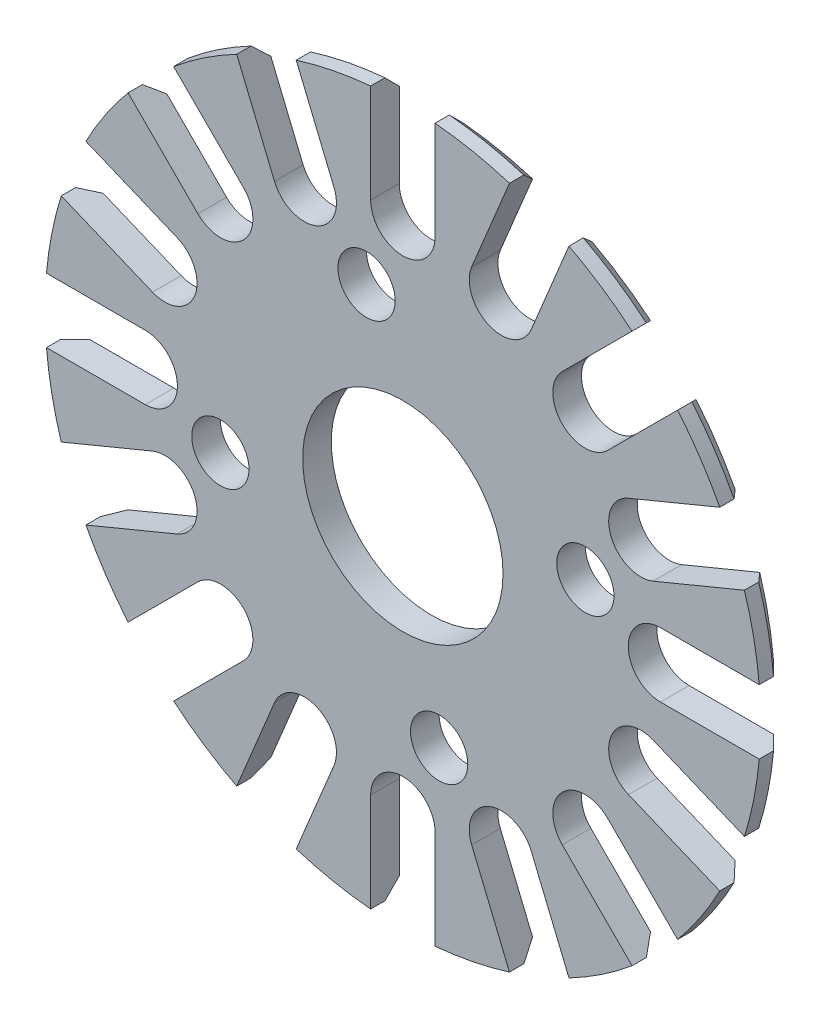
SolidWorks part; units mm, degrees
material "2A12"
ref_plane "前视基准面" through (0, 0, 0) normal (0, 0, 1) x (1, 0, 0)
ref_plane "上视基准面" through (0, 0, 0) normal (0, 1, 0) x (1, 0, 0)
ref_plane "右视基准面" through (0, 0, 0) normal (1, 0, 0) x (0, 0, -1)
sketch "草图1" plane through (0, 0, 0) normal (0, 0, 1) x (1, 0, 0)
  circle A0 centre (0, 0) radius 25
  dimension "D1" = 50
extrude "拉伸1" add sketch "草图1" along normal blind 2
sketch "草图2" plane through (0, 0, 2) normal (0, 0, 1) x (1, 0, 0)
  circle A0 centre (0, 0) radius 7
  dimension "D1" = 14
extrude "拉伸2" cut sketch "草图2" against normal blind 3
sketch "草图3" plane through (0, 0, 2) normal (0, 0, 1) x (1, 0, 0)
  line L0 (-2.5362, 12.7502) -> (0, 0) construction
  line L1 (0, 0) -> (0, 13) construction
  circle A0 centre (-2.5362, 12.7502) radius 2
  circle A1 centre (0, 0) radius 13 construction
  dimension "D1" = 26
  dimension "D2" = 4
  dimension "D3" = 11.25
extrude "拉伸3" cut sketch "草图3" against normal blind 3
pattern_circular "阵列(圆周)1" count 4 every 90 about axis through (0, 0, 0) along (0, 0, 1) of "拉伸3"
chamfer "倒角1" distance 1 angle 45 1 edges at (25, 0, 0)
sketch "草图4" plane through (0, 0, 2) normal (0, 0, 1) x (1, 0, 0)
  line L0 (-18, 2.25) -> (-24.8985, 2.25)
  line L1 (-18, -2.25) -> (-24.8985, -2.25)
  circle A0 centre (0, 0) radius 18 construction
  arc A1 (-18, -2.25) -> (-18, 2.25) centre (-18, 0) ccw
  circle A2 centre (0, 0) radius 25 construction
  arc A4 (-24.8985, 2.25) -> (-24.8985, -2.25) centre (0, 0) ccw
  dimension "D1" = 36
  dimension "D2" = 4.5
extrude "拉伸4" cut sketch "草图4" against normal blind 3
pattern_circular "阵列(圆周)3" count 16 over 360 about axis through (0, 0, 0) along (0, 0, 1) of "拉伸4"
